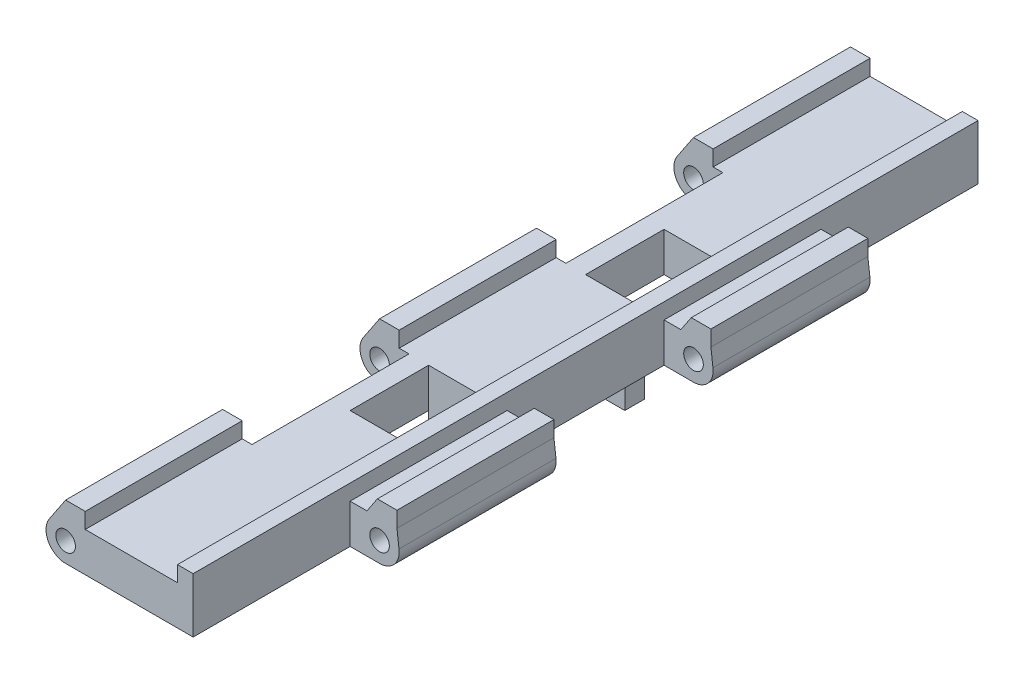
SolidWorks part; units mm, degrees
ref_plane "前视基准面" through (0, 0, 0) normal (0, 0, 1) x (1, 0, 0)
ref_plane "上视基准面" through (0, 0, 0) normal (0, 1, 0) x (1, 0, 0)
ref_plane "右视基准面" through (0, 0, 0) normal (1, 0, 0) x (0, 0, -1)
sketch "草图2" plane through (0, 0, 0) normal (0, 0, 1) x (1, 0, 0)
  line L0 (-1.6556, 0) -> (6.3444, 0)
  line L1 (-1.6556, 2) -> (6.3444, 2)
  arc A0 (-1.6556, 2) -> (-1.6556, 0) centre (-1.6556, 1) ccw
  arc A1 (6.3444, 0) -> (6.3444, 2) centre (6.3444, 1) ccw
  dimension "D2" = 1
  dimension "D3" = 1
  dimension "D1" = 8
  dimension "D4" = 2
extrude "凸台-拉伸1" add sketch "草图2" along normal blind 40
sketch "草图3" plane through (0, 0, 40) normal (0, 0, 1) x (1, 0, 0)
  circle A0 centre (-1.6556, 1) radius 0.5
  circle A1 centre (6.3444, 1.0206) radius 0.5
  dimension "D1" = 8
  dimension "D2" = 1
  dimension "D3" = 1
extrude "切除-拉伸1" cut sketch "草图3" against normal blind 40
sketch "草图11" plane through (0, 0, 40) normal (0, 0, 1) x (1, 0, 0)
  line L1 (-1.6556, 2.8) -> (-0.6556, 2.8)
  line L2 (-0.6556, 2.8) -> (-0.6556, 2)
  line L3 (6.3444, 2) -> (-1.6556, 2) construction
  line L4 (-0.6556, 2) -> (-1.6556, 2)
  line L5 (-1.6556, 2.8) -> (-2.4871, 1.5556)
  arc A0 (-1.6556, 2) -> (-1.6556, 0) centre (-1.6556, 1) ccw construction
  arc A2 (-1.6556, 2) -> (-2.4871, 1.5556) centre (-1.6556, 1) ccw
  dimension "D2" = 1
  dimension "D1" = 0.8
  dimension "D3" = 1
extrude "凸台-拉伸5" add sketch "草图11" against normal blind 40
sketch "草图12" plane through (0, 0, 40) normal (0, 0, 1) x (1, 0, 0)
  line L3 (6.2318, 1.9936) -> (5.7015, 2)
  line L7 (6.2318, 2.7936) -> (7.2318, 2.7936)
  line L8 (7.2318, 2.7936) -> (7.2318, 1.9936)
  line L9 (6.457, 1.9936) -> (6.2318, 1.9936)
  line L10 (6.2318, 2.7936) -> (5.7015, 2)
  line L11 (7.2318, 1.9936) -> (7.3354, 1.1342)
  line L12 (6.3444, 2) -> (-0.6556, 2) construction
  arc A3 (7.3354, 1.1342) -> (6.457, 1.9936) centre (6.3444, 1) ccw
  dimension "D4" = 0.8
extrude "凸台-拉伸6" add sketch "草图12" against normal blind 40
sketch "草图14" plane through (0, 0, 0) normal (0, 1, 0) x (1, 0, 0)
  line L0 (-2.6556, -8) -> (-0.1556, -8)
  line L1 (-2.6556, 0) -> (-2.6556, -40) construction
  line L2 (-0.1556, -8) -> (-0.1556, -16)
  line L3 (-0.1556, -16) -> (-2.6556, -16)
  line L4 (-2.6556, -16) -> (-2.6556, -8)
  line L8 (-2.6556, -32) -> (-2.6556, -24)
  line L9 (-2.6556, -24) -> (-0.1556, -24)
  line L10 (-0.1556, -24) -> (-0.1556, -32)
  line L11 (-0.1556, -32) -> (-2.6556, -32)
  line L12 (5.7015, -40) -> (-0.6556, -40) construction
  line L13 (7.3444, 0) -> (4.8444, 0)
  line L15 (7.3444, 0) -> (6.3444, 0) construction
  line L16 (7.3444, -40) -> (7.3444, 0) construction
  line L17 (5.7015, 0) -> (-0.6556, 0) construction
  line L18 (4.8444, 0) -> (4.8444, -8)
  line L19 (4.8444, -8) -> (7.3444, -8)
  line L20 (7.3444, -8) -> (7.3444, 0)
  line L21 (-0.6556, 0) -> (-1.6556, 0) construction
  line L22 (7.3444, -16) -> (4.8444, -16)
  line L24 (4.8444, -16) -> (4.8444, -24)
  line L25 (4.8444, -24) -> (7.3444, -24)
  line L26 (7.3444, -24) -> (7.3444, -16)
  line L27 (7.3444, -32) -> (4.8444, -32)
  line L28 (4.8444, -32) -> (4.8444, -40)
  line L29 (4.8444, -40) -> (7.3444, -40)
  line L30 (7.3444, -40) -> (7.3444, -32)
  dimension "D1" = 2.5
  dimension "D2" = 8
  dimension "D3" = 8
  dimension "D4" = 2.5
  dimension "D5" = 8
  dimension "D6" = 2.5
  dimension "D7" = 8
  dimension "D8" = 8
  dimension "D9" = 8
  dimension "D10" = 2.5
extrude "切除-拉伸8" cut sketch "草图14" along normal blind 40 contours L4 L0 L2 L3 | L11 L8 L9 L10 | L20 L13 L18 L19 | L26 L22 L24 L25 | L30 L27 L28 L29
sketch "草图15" plane through (0, 2, 0) normal (0, 1, 0) x (1, 0, 0)
  line L0 (-0.6556, -16) -> (-0.6556, -24) construction
  line L1 (0.8444, -16) -> (3.8444, -16)
  line L2 (0.8444, -16) -> (0.8444, -12)
  line L3 (0.8444, -12) -> (3.8444, -12)
  line L4 (3.8444, -16) -> (3.8444, -12)
  line L7 (-2.4871, -20) -> (13.051, -20) construction
  line L8 (-2.4871, -16) -> (-2.4871, -24) construction
  line L9 (3.8444, -24) -> (3.8444, -28)
  line L10 (0.8444, -28) -> (3.8444, -28)
  line L11 (0.8444, -24) -> (0.8444, -28)
  line L12 (0.8444, -24) -> (3.8444, -24)
  dimension "D1" = 3
  dimension "D2" = 4
  dimension "D3" = 1.5
  dimension "D4" = 4
extrude "切除-拉伸9" cut sketch "草图15" against normal through all
sketch "草图16" plane through (0, 0, 40) normal (0, 0, 1) x (1, 0, 0)
  line L0 (4.8444, 2) -> (4.0444, 2)
  line L1 (4.8444, 2) -> (-0.6556, 2) construction
  line L2 (4.0444, 2) -> (4.0444, 2.8)
  line L3 (4.0444, 2.8) -> (4.8444, 2.8)
  line L4 (4.8444, 2.8) -> (4.8444, 2)
  dimension "D1" = 0.8
  dimension "D2" = 0.8
extrude "凸台-拉伸7" add sketch "草图16" against normal blind 40
sketch "草图17" plane through (0, 0, 24) normal (0, 0, 1) x (1, 0, 0)
  line L0 (0.8444, 0) -> (0.8444, -2)
  line L1 (0.8444, -2) -> (3.8444, -2)
  line L2 (3.8444, -2) -> (3.8444, 0)
  line L3 (-1.6556, 0) -> (4.8444, 0) construction
  line L4 (3.8444, 0) -> (0.8444, 0)
  dimension "D1" = 3
  dimension "D2" = 2
extrude "凸台-拉伸8" add sketch "草图17" against normal blind 1
sketch "草图18" plane through (0, 0, 16) normal (0, 0, -1) x (-1, 0, 0)
  line L0 (-3.8444, 0) -> (-3.8444, -2)
  line L1 (-3.8444, -2) -> (-0.8444, -2)
  line L2 (-0.8444, -2) -> (-0.8444, 0)
  line L3 (-0.8444, 0) -> (-3.8444, 0)
extrude "凸台-拉伸9" add sketch "草图18" against normal blind 1
ref_plane "基准面1" through (0, 0, 20) normal (0, 0, -1) x (-1, 0, 0)
equation "\"2。5\"=2.33548"
